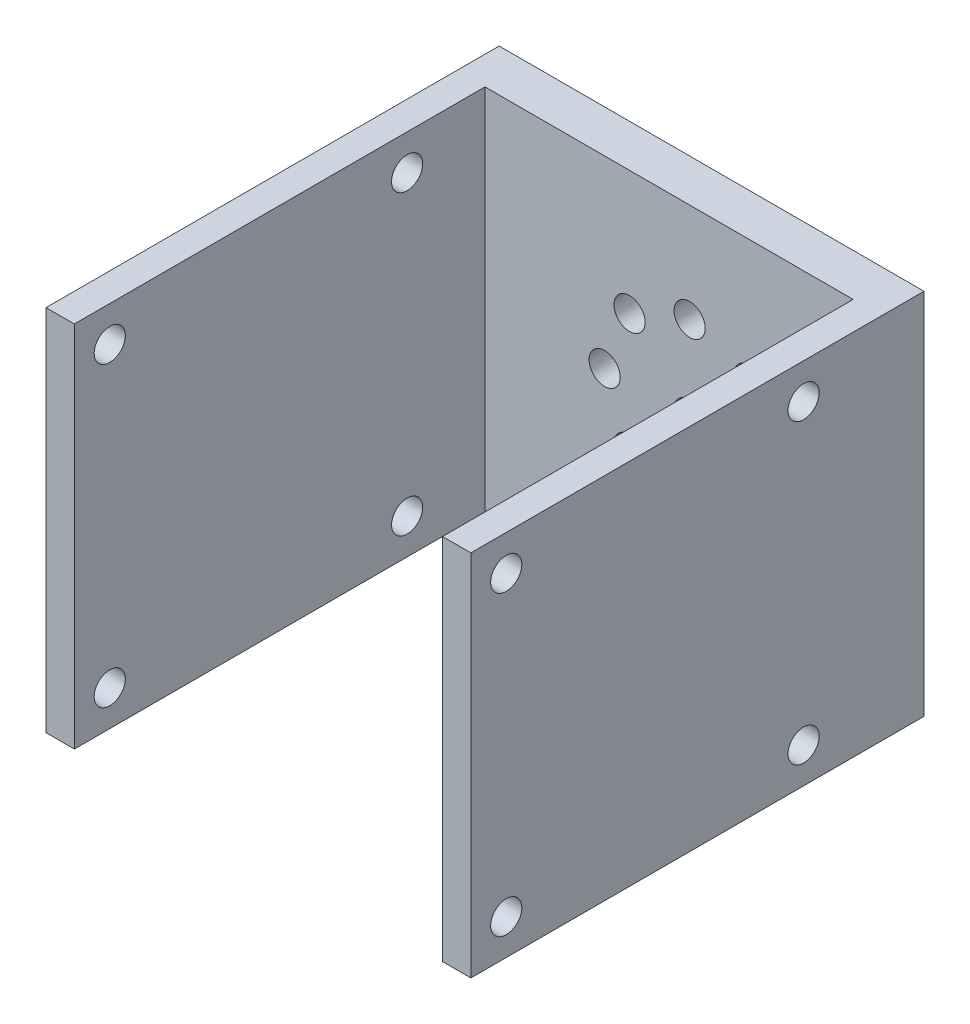
SolidWorks part; units mm, degrees
material "ABS"
ref_plane "正面" through (0, 0, 0) normal (0, 0, 1) x (1, 0, 0)
ref_plane "平面" through (0, 0, 0) normal (0, 1, 0) x (1, 0, 0)
ref_plane "右側面" through (0, 0, 0) normal (1, 0, 0) x (0, 0, -1)
sketch "ｽｹｯﾁ1" plane through (0, 0, 0) normal (0, 0, 1) x (1, 0, 0)
  line L0 (-13, 0) -> (13, 0) construction
  line L5 (-13, 13) -> (13, 13)
  line L6 (-13, 13) -> (-13, -13)
  line L7 (-13, -13) -> (13, -13)
  line L8 (13, 13) -> (13, -13)
  line L9 (-13, 13) -> (13, -13) construction
  line L10 (-13, -13) -> (13, 13) construction
  circle A0 centre (1.45, 0) radius 6 construction
  circle A1 centre (1.45, 0) radius 1.1
  circle A2 centre (1.45, 6) radius 1.1
  circle A3 centre (5.6926, 4.2426) radius 1.1
  circle A4 centre (7.45, 0) radius 1.1
  circle A5 centre (5.6926, -4.2426) radius 1.1
  circle A6 centre (1.45, -6) radius 1.1
  circle A7 centre (-2.7926, -4.2426) radius 1.1
  circle A8 centre (-4.55, 0) radius 1.1
  circle A9 centre (-2.7926, 4.2426) radius 1.1
  point P0 (0, 0)
  point P13 (-0.7692, 5.2976)
  point P14 (0, 0)
  point P30 (1.45, 0)
  dimension "D3" = 2.2
  dimension "D4" = 12
  dimension "D5" = 2.2
  dimension "D1" = 26
  dimension "D2" = 26
  dimension "D7" = 1.45
  dimension "D6" = 8
extrude "ﾎﾞｽ - 押し出し1" add sketch "ｽｹｯﾁ1" along normal blind 3
sketch "ｽｹｯﾁ2" plane through (-13, 0, 0) normal (-1, 0, 0) x (0, 0, 1)
  line L0 (3, -13) -> (0, -13) construction
  line L1 (0, 13) -> (32, 13)
  line L2 (0, 13) -> (0, -13)
  line L3 (0, -13) -> (32, -13)
  line L4 (32, 13) -> (32, -13)
  line L5 (32, 0) -> (0, 0) construction
  line L7 (29.5, 10.5) -> (8.5, 10.5) construction
  line L8 (29.5, 10.5) -> (29.5, -10.5) construction
  line L9 (29.5, -10.5) -> (8.5, -10.5) construction
  line L10 (8.5, 10.5) -> (8.5, -10.5) construction
  line L11 (29.5, 10.5) -> (8.5, -10.5) construction
  line L12 (29.5, -10.5) -> (8.5, 10.5) construction
  circle A0 centre (29.5, 10.5) radius 1.1
  circle A1 centre (8.5, 10.5) radius 1.1
  circle A2 centre (8.5, -10.5) radius 1.1
  circle A3 centre (29.5, -10.5) radius 1.1
  point P9 (19, 0)
  dimension "D2" = 2.2
  dimension "D3" = 32
  dimension "D1" = 21
  dimension "D4" = 13
extrude "ﾎﾞｽ - 押し出し2" add sketch "ｽｹｯﾁ2" along normal blind 2
sketch "ｽｹｯﾁ3" plane through (13, 0, 0) normal (1, 0, 0) x (0, 0, -1)
  line L4 (0, -13) -> (0, 13)
  line L5 (-32, -13) -> (0, -13)
  line L6 (-32, 13) -> (-32, -13)
  line L7 (0, 13) -> (-32, 13)
  line L8 (0, -13) -> (0, 13)
  line L9 (-32, -13) -> (0, -13)
  line L10 (-32, 13) -> (-32, -13)
  line L11 (0, 13) -> (-32, 13)
  circle A0 centre (-8.5, -10.5) radius 1.1 construction
  circle A1 centre (-8.5, 10.5) radius 1.1 construction
  circle A2 centre (-29.5, 10.5) radius 1.1 construction
  circle A3 centre (-29.5, -10.5) radius 1.1 construction
  circle A4 centre (-8.5, -10.5) radius 1.1
  circle A5 centre (-8.5, 10.5) radius 1.1
  circle A6 centre (-29.5, 10.5) radius 1.1
  circle A7 centre (-29.5, -10.5) radius 1.1
  dimension "D1" = 0
extrude "ﾎﾞｽ - 押し出し3" add sketch "ｽｹｯﾁ3" along normal blind 2
